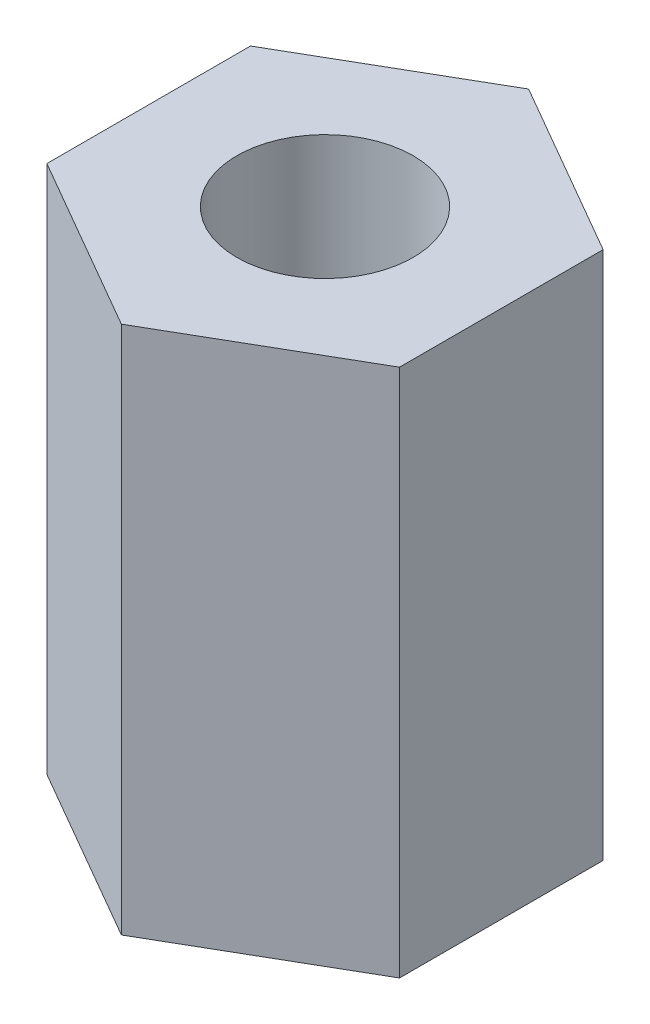
SolidWorks part; units mm, degrees
ref_plane "前视基准面" through (0, 0, 0) normal (0, 0, 1) x (1, 0, 0)
ref_plane "上视基准面" through (0, 0, 0) normal (0, 1, 0) x (1, 0, 0)
ref_plane "右视基准面" through (0, 0, 0) normal (1, 0, 0) x (0, 0, -1)
sketch "草图1" plane through (0, 0, 0) normal (0, 1, 0) x (1, 0, 0)
  line L1 (2, -1.1547) -> (2, 1.1547)
  line L2 (2, 1.1547) -> (0, 2.3094)
  line L3 (0, 2.3094) -> (-2, 1.1547)
  line L4 (-2, 1.1547) -> (-2, -1.1547)
  line L5 (-2, -1.1547) -> (0, -2.3094)
  line L6 (0, -2.3094) -> (2, -1.1547)
  circle A0 centre (0, 0) radius 2 construction
  circle A1 centre (0, 0) radius 1
  point P1 (0, 0)
  dimension "D2" = 2
  dimension "D1" = 4
extrude "凸台-拉伸1" add sketch "草图1" along normal blind 6
